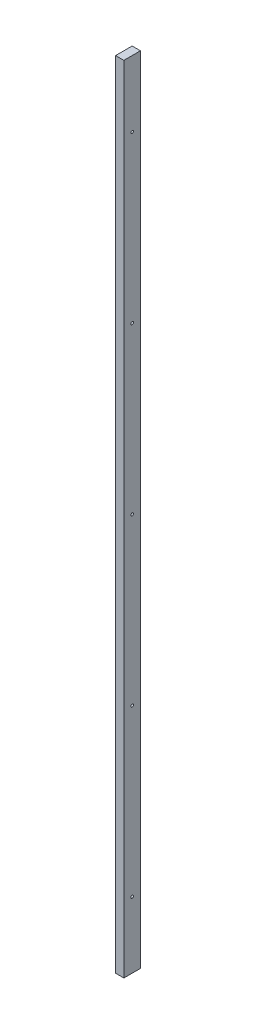
SolidWorks part; units mm, degrees
ref_plane "Спереди" through (0, 0, 0) normal (0, 0, 1) x (1, 0, 0)
ref_plane "Сверху" through (0, 0, 0) normal (0, 1, 0) x (1, 0, 0)
ref_plane "Справа" through (0, 0, 0) normal (1, 0, 0) x (0, 0, -1)
other "Configuration Table"
sketch "Эскиз1" plane through (0, 0, 0) normal (0, 1, 0) x (1, 0, 0)
  line L1 (12.5, 25) -> (-12.5, 25)
  line L2 (12.5, 25) -> (12.5, -25)
  line L3 (12.5, -25) -> (-12.5, -25)
  line L4 (-12.5, 25) -> (-12.5, -25)
  line L5 (12.5, 25) -> (-12.5, -25) construction
  line L6 (12.5, -25) -> (-12.5, 25) construction
  point P0 (0, 0)
extrude "Бобышка-Вытянуть1" add sketch "Эскиз1" along normal blind 2400
sketch "Эскиз2" plane through (12.5, 0, 0) normal (1, 0, 0) x (0, 0, -1)
  line L0 (0, 0) -> (0, 200) construction
  line L1 (0, 200) -> (0, 700) construction
  line L2 (0, 700) -> (0, 1200) construction
  line L3 (0, 1200) -> (0, 1700) construction
  line L4 (0, 1700) -> (0, 2200) construction
  line L5 (0, 2200) -> (0, 2400) construction
  line L6 (-25, 2400) -> (25, 2400) construction
  circle A0 centre (0, 2200) radius 4
  circle A1 centre (0, 1700) radius 4
  circle A2 centre (0, 1200) radius 4
  circle A3 centre (0, 700) radius 4
  circle A4 centre (0, 200) radius 4
extrude "Вырез-Вытянуть1" cut sketch "Эскиз2" against normal blind 2400
